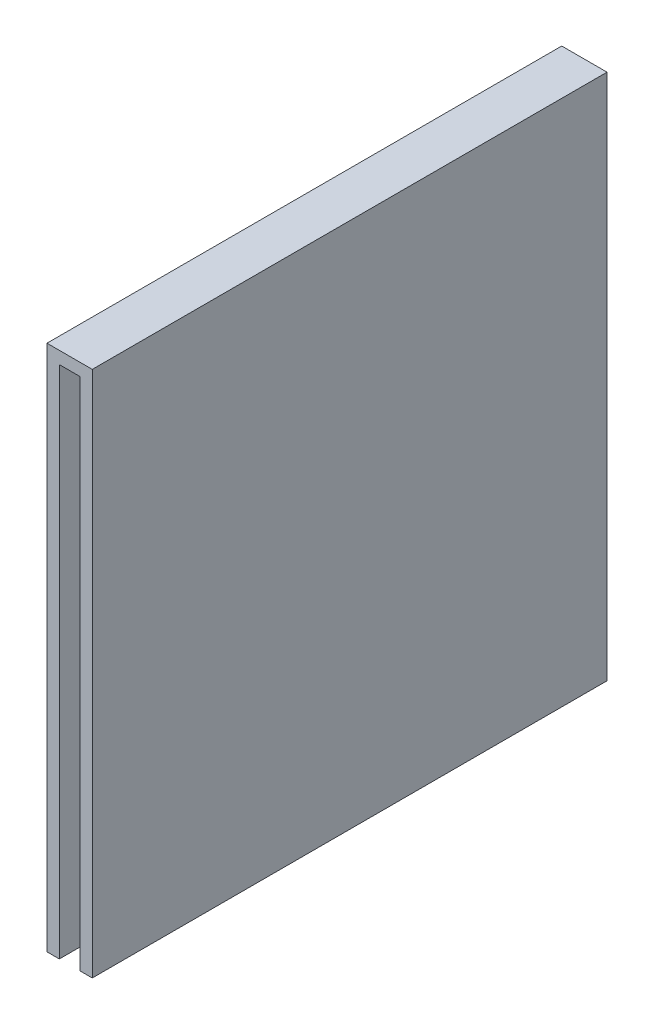
SolidWorks part; units mm, degrees
ref_plane "Plan de face" through (0, 0, 0) normal (0, 0, 1) x (1, 0, 0)
ref_plane "Plan de dessus" through (0, 0, 0) normal (0, 1, 0) x (1, 0, 0)
ref_plane "Plan de droite" through (0, 0, 0) normal (1, 0, 0) x (0, 0, -1)
sketch "Esquisse1" plane through (0, 0, 0) normal (0, 0, 1) x (1, 0, 0)
  line L0 (-15.5104, -19.5121) -> (-15.5104, -7.0121)
  line L1 (-15.5104, -7.0121) -> (-15.0104, -7.0121)
  line L2 (-15.0104, -7.0121) -> (-15.0104, -19.5121)
  line L3 (-15.0104, -19.5121) -> (-14.7104, -19.5121)
  line L4 (-15.5104, -19.5121) -> (-15.8104, -19.5121)
  line L5 (-15.8104, -6.7121) -> (-14.7104, -6.7121)
  line L6 (-15.8104, -6.7121) -> (-15.8104, -19.5121)
  line L7 (-14.7104, -6.7121) -> (-14.7104, -19.5121)
  dimension "D1" = 0.3
extrude "Extrusion1" add sketch "Esquisse1" along normal blind 12.5
